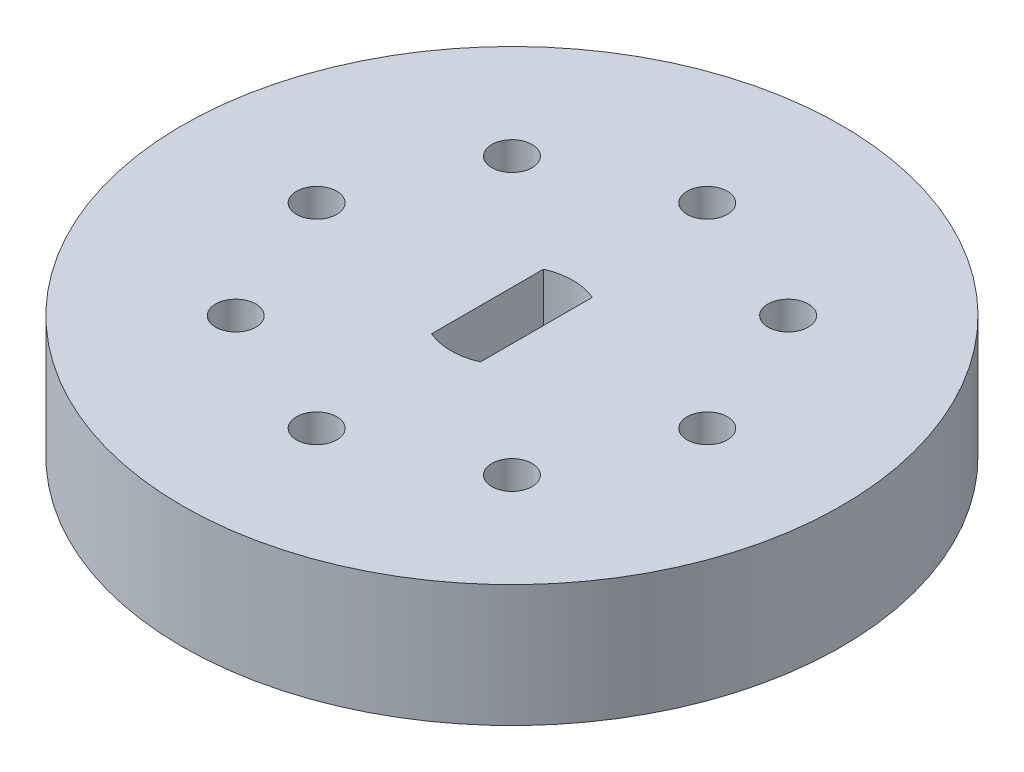
SolidWorks part; units mm, degrees
material "PTFE (general)"
ref_plane "Front Plane" through (0, 0, 0) normal (0, 0, 1) x (1, 0, 0)
ref_plane "Top Plane" through (0, 0, 0) normal (0, 1, 0) x (1, 0, 0)
ref_plane "Right Plane" through (0, 0, 0) normal (1, 0, 0) x (0, 0, -1)
sketch "Sketch1" plane through (0, 0, 0) normal (0, 1, 0) x (1, 0, 0)
  circle A0 centre (0, 0) radius 27
  dimension "D1" = 54
extrude "Boss-Extrude1" add sketch "Sketch1" along normal blind 10
sketch "Sketch2" plane through (0, 10, 0) normal (0, 1, 0) x (1, 0, 0)
  line L0 (-2, 4.5826) -> (-2, -4.5826)
  line L2 (2, -4.5826) -> (2, 4.5826)
  line L4 (0, 5) -> (0, -5) construction
  arc A0 (-2, -4.5826) -> (2, -4.5826) centre (0, 0) ccw
  arc A1 (2, 4.5826) -> (-2, 4.5826) centre (0, 0) ccw
  point P5 (-2, 0)
  dimension "D1" = 10
  dimension "D2" = 4
extrude "Cut-Extrude1" cut sketch "Sketch2" against normal up to surface (10 mm away) up to face at (0, 0, 27)
sketch "Sketch3" plane through (0, 10, 0) normal (0, 1, 0) x (1, 0, 0)
  circle A0 centre (16, 0) radius 1.65
  circle A1 centre (11.3137, -11.3137) radius 1.65
  circle A2 centre (0, -16) radius 1.65
  circle A3 centre (-11.3137, -11.3137) radius 1.65
  circle A4 centre (-16, 0) radius 1.65
  circle A5 centre (-11.3137, 11.3137) radius 1.65
  circle A6 centre (0, 16) radius 1.65
  circle A7 centre (11.3137, 11.3137) radius 1.65
  point P19 (0, 0)
  dimension "D1" = 3.3
  dimension "D2" = 16
  dimension "D3" = 8
extrude "Cut-Extrude2" cut sketch "Sketch3" against normal up to surface (10 mm away) up to face at (0, 0, 0)
